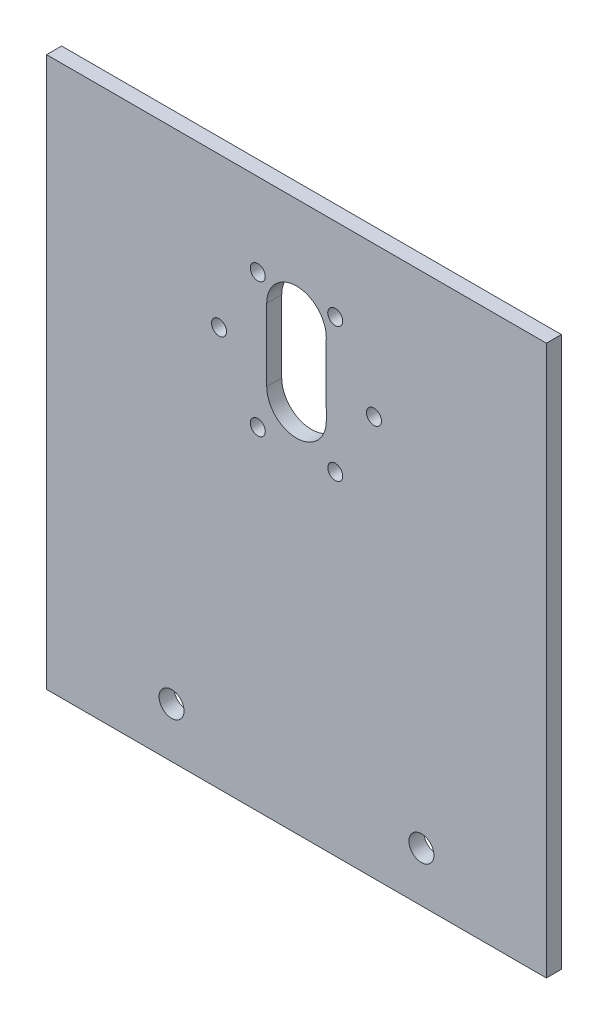
SolidWorks part; units mm, degrees
ref_plane "Front Plane" through (0, 0, 0) normal (0, 0, 1) x (1, 0, 0)
ref_plane "Top Plane" through (0, 0, 0) normal (0, 1, 0) x (1, 0, 0)
ref_plane "Right Plane" through (0, 0, 0) normal (1, 0, 0) x (0, 0, -1)
sketch "Sketch1" plane through (0, 0, 0) normal (0, 0, 1) x (1, 0, 0)
  line L4 (0, 55) -> (0, 39.9045) construction
  line L13 (50, -55) -> (-50, -55)
  line L14 (50, -55) -> (50, 55)
  line L15 (50, 55) -> (-50, 55)
  line L16 (-50, -55) -> (-50, 55)
  line L17 (50, -55) -> (-50, 55) construction
  line L18 (50, 55) -> (-50, -55) construction
  line L19 (5.9109, 33.1851) -> (5.9595, 19.5268)
  line L26 (-5.9595, 33.945) -> (-5.9595, 19.5056)
  circle A16 centre (-25, -45) radius 2.5
  circle A17 centre (25, -45) radius 2.5
  circle A26 centre (-15.5, 24.9972) radius 1.5
  circle A27 centre (-7.7524, 38.422) radius 1.5
  circle A28 centre (7.7476, 38.4248) radius 1.5
  circle A29 centre (15.5, 25.0028) radius 1.5
  circle A30 centre (7.7524, 11.578) radius 1.5
  circle A31 centre (-7.7476, 11.5752) radius 1.5
  arc A33 (-5.9595, 19.5056) -> (5.9595, 19.5268) centre (0, 19.5056) ccw
  arc A35 (5.9109, 33.1851) -> (-5.9595, 33.945) centre (0, 33.945) ccw
  point P0 (0, 0)
  point P2 (0, 25.0389)
  point P6 (-6.049, 33.8498)
  point P7 (-6.0449, 33.945)
  point P15 (47.5, 80)
  point P29 (0, 25.0389)
  point P32 (0, 34.1337)
  point P37 (0, 25)
  dimension "D5" = 5
  dimension "D6" = 5
  dimension "D4" = 15.5
  dimension "D12" = 31
  dimension "D11" = 3
  dimension "D1" = 100
  dimension "D2" = 110
  dimension "D7" = 6
  dimension "50" = 50
  dimension "25" = 25
  dimension "D9" = 10
  dimension "D10" = 10
extrude "Boss-Extrude1" add sketch "Sketch1" along normal blind 3
